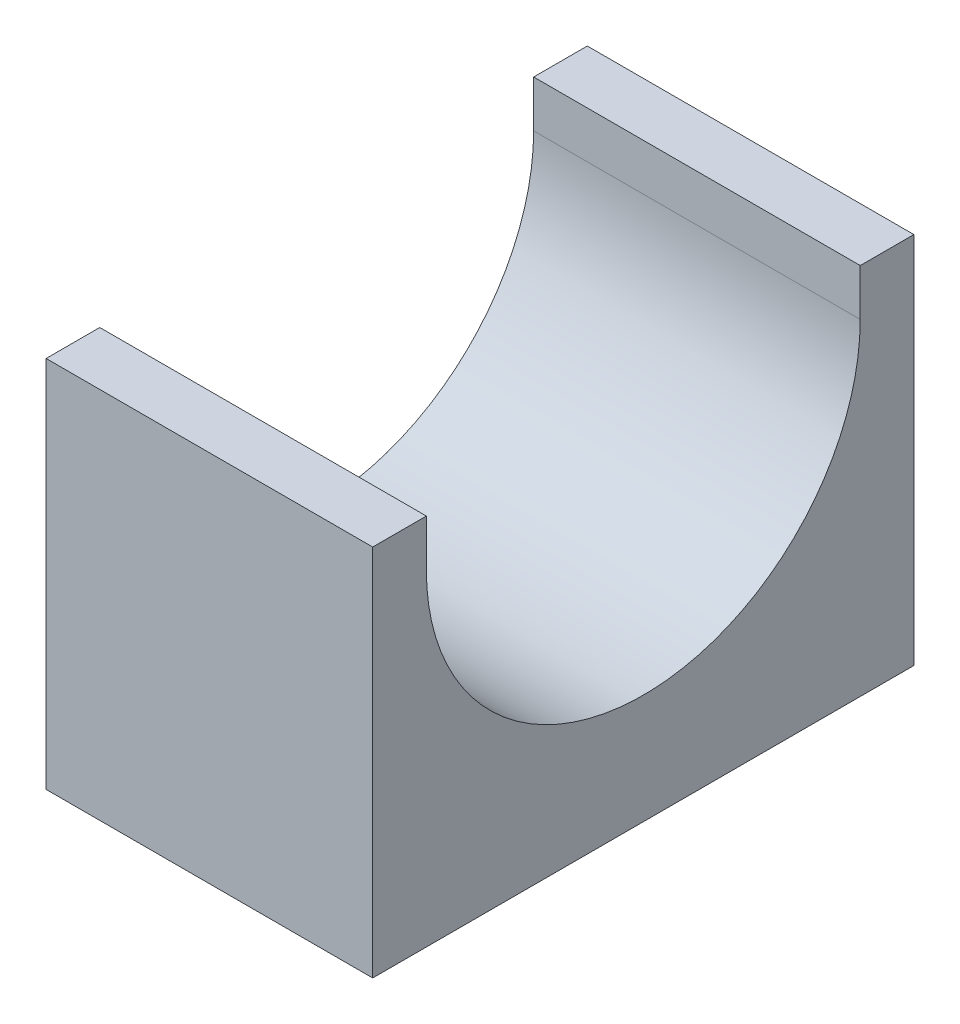
SolidWorks part; units mm, degrees
ref_plane "Front Plane" through (0, 0, 0) normal (0, 0, 1) x (1, 0, 0)
ref_plane "Top Plane" through (0, 0, 0) normal (0, 1, 0) x (1, 0, 0)
ref_plane "Right Plane" through (0, 0, 0) normal (1, 0, 0) x (0, 0, -1)
sketch "Sketch1" plane through (0, 0, 0) normal (0, 1, 0) x (1, 0, 0)
  line L1 (-17.5, -29) -> (17.5, -29)
  line L2 (-17.5, -29) -> (-17.5, 29)
  line L3 (-17.5, 29) -> (17.5, 29)
  line L4 (17.5, -29) -> (17.5, 29)
  line L5 (-17.5, -29) -> (17.5, 29) construction
  line L6 (-17.5, 29) -> (17.5, -29) construction
  point P0 (0, 0)
  dimension "D1" = 35
  dimension "D2" = 58
extrude "Boss-Extrude1" add sketch "Sketch1" along normal blind 40
sketch "Sketch2" plane through (17.5, 0, 0) normal (1, 0, 0) x (0, 0, -1)
  line L1 (-29, 40) -> (29, 40) construction
  line L4 (-23.25, 35) -> (-23.25, 58.25)
  line L5 (-23.25, 58.25) -> (23.25, 58.25)
  line L6 (23.25, 35) -> (23.25, 58.25)
  arc A0 (-23.25, 35) -> (23.25, 35) centre (0, 35) ccw
  dimension "D1" = 46.5
  dimension "D2" = 5
extrude "Cut-Extrude1" cut sketch "Sketch2" against normal through all
